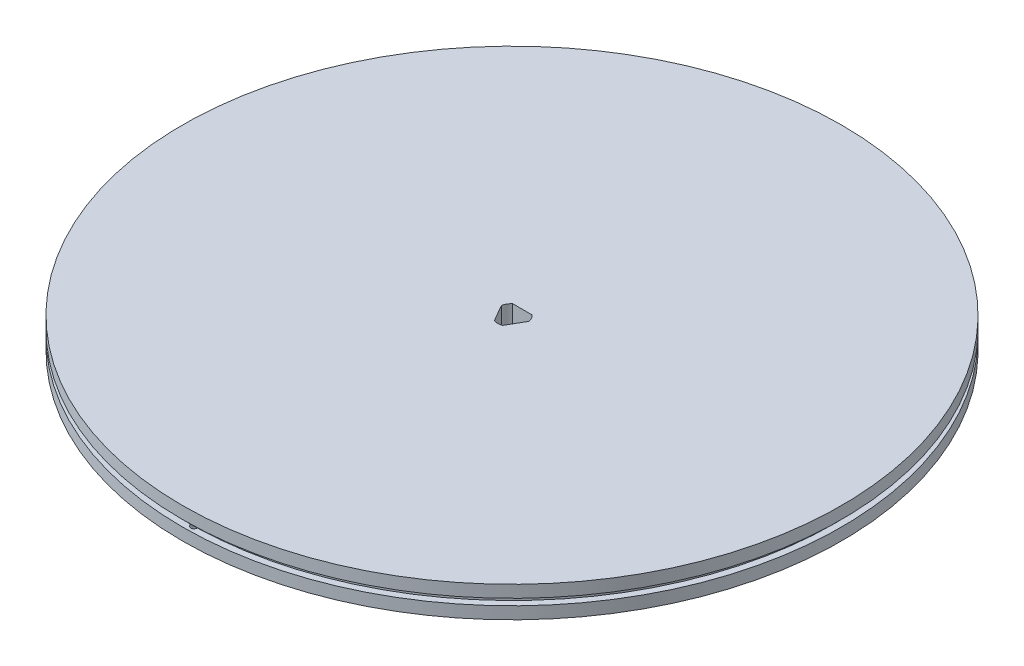
SolidWorks part; units mm, degrees
material "ABS"
ref_plane "Plano frontal" through (0, 0, 0) normal (0, 0, 1) x (1, 0, 0)
ref_plane "Plano superior" through (0, 0, 0) normal (0, 1, 0) x (1, 0, 0)
ref_plane "Plano direito" through (0, 0, 0) normal (1, 0, 0) x (0, 0, -1)
sketch "Esboço1" plane through (0, 0, 0) normal (0, 1, 0) x (1, 0, 0)
  circle A0 centre (0, 0) radius 51
  dimension "D1" = 102
extrude "Ressalto-extrusão1" add sketch "Esboço1" along normal mid plane 4.7625
sketch "Esboço2" plane through (0, 0, 0) normal (0, 1, 0) x (1, 0, 0)
  circle A0 centre (0, 0) radius 50
  circle A1 centre (0, 0) radius 51
  circle A2 centre (0, 0) radius 51 construction
  dimension "D1" = 100
extrude "Corte-extrusão1" cut sketch "Esboço2" against normal mid plane 1
sketch "Esboço3" plane through (0, -0.5, 0) normal (0, 1, 0) x (1, 0, 0)
  line L0 (0, 0) -> (0.7895, -50) construction
  circle A0 centre (0.7895, -50) radius 0.5
  dimension "D2" = 1
  dimension "D1" = 50
extrude "Corte-extrusão2" cut sketch "Esboço3" against normal up to surface (1.8813 mm away) up to face at (0, -2.3813, 51)
sketch "Esboço4" plane through (0, 2.3813, 0) normal (0, 1, 0) x (1, 0, 0)
  line L0 (-2.1406, 0.5077) -> (-0.6307, -2.1077)
  line L1 (0.6307, -2.1077) -> (2.1406, 0.5077)
  line L2 (1.51, 1.6) -> (-1.51, 1.6)
  line L3 (-1.3856, -0.8) -> (1.9053, 1.1) construction
  line L4 (0, 1.6) -> (0, -2.2) construction
  arc A0 (-1.51, 1.6) -> (-2.1406, 0.5077) centre (0, 0) ccw
  arc A1 (-0.6307, -2.1077) -> (0.6307, -2.1077) centre (0, 0) ccw
  arc A2 (1.51, 1.6) -> (2.1406, 0.5077) centre (0, 0) cw
  dimension "D1" = 2.2
  dimension "D2" = 3.8
extrude "Corte-extrusão3" cut sketch "Esboço4" against normal through all
